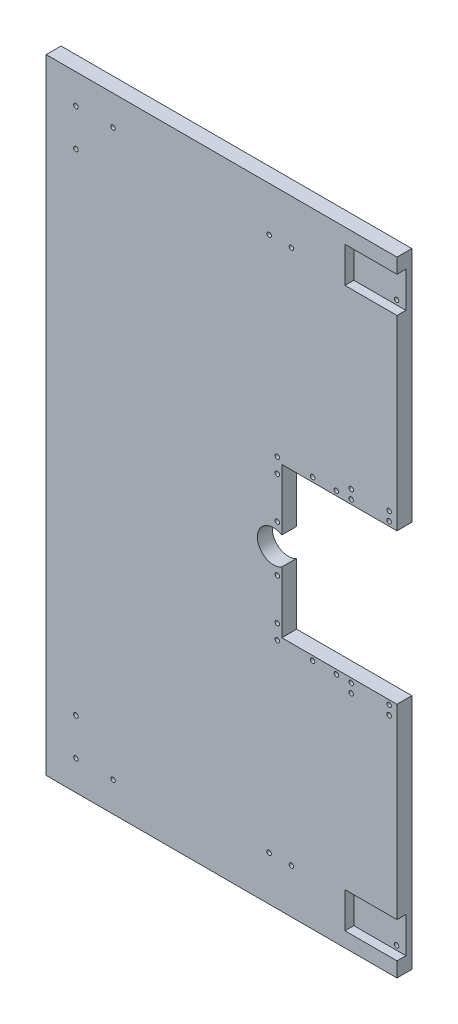
SolidWorks part; units mm, degrees
ref_plane "前视基准面" through (0, 0, 0) normal (0, 0, 1) x (1, 0, 0)
ref_plane "上视基准面" through (0, 0, 0) normal (0, 1, 0) x (1, 0, 0)
ref_plane "右视基准面" through (0, 0, 0) normal (1, 0, 0) x (0, 0, -1)
sketch "草图1" plane through (0, 0, 0) normal (0, 0, 1) x (1, 0, 0)
  line L1 (-118, 210) -> (118, 210)
  line L2 (-118, 210) -> (-118, -210)
  line L3 (-118, -210) -> (118, -210)
  line L4 (118, 210) -> (118, 50.5)
  line L5 (-118, 210) -> (118, -210) construction
  line L6 (-118, -210) -> (118, 210) construction
  line L7 (118, -50.5) -> (40.5, -50.5)
  line L12 (40.5, -9.3341) -> (40.5, -50.5)
  line L14 (118, -50.5) -> (118, -210)
  line L17 (40.5, 50.5) -> (118, 50.5)
  line L22 (0, 0) -> (61, 0) construction
  line L24 (79, 0) -> (133.002, 0) construction
  line L59 (40.5, 9.3341) -> (40.5, 50.5)
  arc A23 (40.5, 9.3341) -> (40.8223, -9.135) centre (34.956, 0) ccw
  point P0 (0, 0)
  point P9 (118, 0)
  dimension "D3" = 77.5
  dimension "D4" = 77.5
  dimension "D1" = 236
  dimension "D2" = 420
extrude "凸台-拉伸1" add sketch "草图1" along normal blind 10
sketch "草图2" plane through (0, 0, 10) normal (0, 0, 1) x (1, 0, 0)
  line L0 (-118, 210) -> (-118, -210) construction
  line L2 (-98, 165) -> (-98, 190) construction
  line L3 (-98, 190) -> (-73, 190) construction
  line L5 (-98, 165) -> (-73, 190) construction
  line L7 (-118, 210) -> (118, 210) construction
  circle A0 centre (-98, 165) radius 1.5
  circle A1 centre (-73, 190) radius 1.5
  circle A2 centre (-98, 190) radius 1.5
  point P0 (-86.9005, 176.0995)
  dimension "D1" = 25
  dimension "D2" = 25
  dimension "D3" = 20
  dimension "D4" = 20
extrude "切除-拉伸1" cut sketch "草图2" against normal blind 10
sketch "草图3" plane through (0, 0, 10) normal (0, 0, 1) x (1, 0, 0)
  line L1 (40.5, -9.3341) -> (40.5, -50.5) construction
  line L2 (40.5, -9.3341) -> (40.5, -50.5) construction
  line L3 (0, 0) -> (125.1957, 0) construction
  line L4 (112.73, -53.5) -> (112.73, -59.5) construction
  line L5 (112.73, -59.5) -> (87.23, -59.5) construction
  line L6 (87.23, -59.5) -> (87.23, -53.5) construction
  line L7 (87.23, -53.5) -> (77.23, -53.5) construction
  line L8 (77.23, -53.5) -> (61.23, -53.5) construction
  line L9 (61.23, -53.5) -> (37.5, -53.5) construction
  line L10 (37.5, -53.5) -> (37.5, -43.5) construction
  line L11 (87.23, -53.5) -> (112.73, -53.5) construction
  line L12 (118, -50.5) -> (40.5, -50.5) construction
  line L13 (118, -50.5) -> (118, -210) construction
  circle A1 centre (37.5, -15.6728) radius 1.5
  circle A2 centre (112.73, -53.5) radius 1.5
  circle A3 centre (112.73, -59.5) radius 1.5
  circle A4 centre (87.23, -53.5) radius 1.5
  circle A5 centre (87.23, -59.5) radius 1.5
  circle A6 centre (77.23, -53.5) radius 1.5
  circle A7 centre (61.23, -53.5) radius 1.5
  circle A8 centre (37.5, -53.5) radius 1.5
  circle A9 centre (37.5, -43.5) radius 1.5
  dimension "D2" = 3
  dimension "D4" = 3
  dimension "D5" = 3
  dimension "D6" = 3
  dimension "D7" = 3
  dimension "D8" = 3
  dimension "D9" = 3
  dimension "D10" = 3
  dimension "D11" = 3
  dimension "D3" = 3
  dimension "D12" = 3
  dimension "D13" = 5.27
  dimension "D14" = 25.5
  dimension "D15" = 10
  dimension "D16" = 6
  dimension "D17" = 16
  dimension "D18" = 3
  dimension "D19" = 10
extrude "切除-拉伸2" cut sketch "草图3" against normal blind 10
mirror "镜向1" about plane through (0, 0, 0) normal (0, 1, 0) of "切除-拉伸2"
mirror "镜向2" about plane through (0, 0, 0) normal (0, 1, 0) of "切除-拉伸1"
sketch "草图4" plane through (0, 0, 10) normal (0, 0, 1) x (1, 0, 0)
  line L0 (32, 180) -> (47, 180) construction
  line L1 (-118, 210) -> (118, 210) construction
  line L2 (-118, 210) -> (-118, -210) construction
  circle A0 centre (32, 180) radius 1.5
  circle A1 centre (47, 180) radius 1.5
  dimension "D1" = 3
  dimension "D2" = 3
  dimension "D3" = 30
  dimension "D4" = 150
  dimension "D5" = 15
extrude "切除-拉伸3" cut sketch "草图4" against normal blind 10
mirror "镜向3" about plane through (0, 0, 0) normal (0, 1, 0) of "切除-拉伸3"
sketch "草图5" plane through (0, 0, 10) normal (0, 0, 1) x (1, 0, 0)
  line L0 (118, -50.5) -> (118, -210) construction
  line L1 (83, -176) -> (118, -176)
  line L2 (83, -176) -> (83, -200)
  line L3 (83, -200) -> (118, -200)
  line L4 (118, -176) -> (118, -200)
  line L5 (-118, -210) -> (118, -210) construction
  line L6 (100.5, -176) -> (100.5, -200) construction
  dimension "D1" = 35
  dimension "D2" = 24
  dimension "D3" = 10
extrude "切除-拉伸4" cut sketch "草图5" against normal blind 6
sketch "草图6" plane through (0, 0, 4) normal (0, 0, 1) x (1, 0, 0)
  line L0 (111.75, -179) -> (111.75, -197) construction
  line L1 (118, -176) -> (83, -176) construction
  line L3 (83, -200) -> (118, -200) construction
  line L4 (118, -200) -> (118, -176) construction
  circle A0 centre (111.75, -179) radius 1.5
  circle A1 centre (111.75, -197) radius 1.5
  dimension "D1" = 3
  dimension "D2" = 3
  dimension "D3" = 3
  dimension "D4" = 3
  dimension "D5" = 6.25
extrude "切除-拉伸5" cut sketch "草图6" against normal through all
mirror "镜向4" about plane through (0, 0, 0) normal (0, 1, 0) of "切除-拉伸5", "切除-拉伸4"
